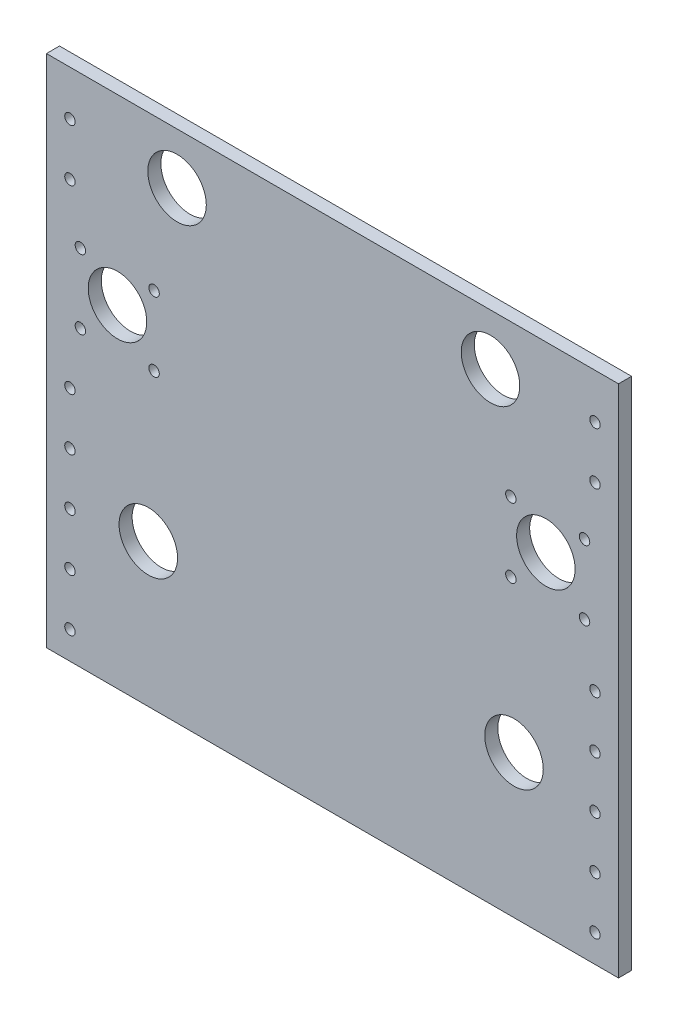
SolidWorks part; units mm, degrees
ref_plane "Front Plane" through (0, 0, 0) normal (0, 0, 1) x (1, 0, 0)
ref_plane "Top Plane" through (0, 0, 0) normal (0, 1, 0) x (1, 0, 0)
ref_plane "Right Plane" through (0, 0, 0) normal (1, 0, 0) x (0, 0, -1)
sketch "Sketch1" plane through (0, 0, 0) normal (0, 0, 1) x (1, 0, 0)
  line L1 (0, 0) -> (278.13, 0)
  line L2 (0, 0) -> (0, 250.19)
  line L3 (0, 250.19) -> (278.13, 250.19)
  line L4 (278.13, 0) -> (278.13, 250.19)
  dimension "D1" = 278.13
  dimension "D2" = 250.19
extrude "Boss-Extrude1" add sketch "Sketch1" along normal blind 6.35 contours L2 L1 L4 L3
sketch "Sketch2" plane through (0, 0, 6.35) normal (0, 0, 1) x (1, 0, 0)
  circle A0 centre (78.4492, 218.0515) radius 20.3285
  circle A1 centre (197.8327, 207.7025) radius 26.984
sketch "Sketch3" plane through (0, 0, 6.35) normal (0, 0, 1) x (1, 0, 0)
  line L0 (63.5, 225.298) -> (215.9, 225.298) construction
  line L1 (34.544, 161.544) -> (242.824, 161.544) construction
  line L2 (49.53, 69.596) -> (227.33, 69.596) construction
  line L3 (0, 250.19) -> (278.13, 250.19) construction
  line L5 (278.13, 0) -> (278.13, 250.19) construction
  line L6 (0, 0) -> (0, 250.19) construction
  circle A0 centre (63.5, 225.298) radius 14.224
  circle A1 centre (215.9, 225.298) radius 14.224
  circle A2 centre (34.544, 161.544) radius 14.224
  circle A3 centre (242.824, 161.544) radius 14.224
  circle A4 centre (49.53, 69.596) radius 14.224
  circle A5 centre (227.33, 69.596) radius 14.224
  dimension "D1" = 28.448
  dimension "D2" = 152.4
  dimension "D3" = 208.28
  dimension "D4" = 177.8
  dimension "D5" = 24.892
  dimension "D6" = 62.23
  dimension "D7" = 34.544
  dimension "D8" = 88.646
  dimension "D9" = 49.53
  dimension "D10" = 180.594
extrude "Cut-Extrude2" cut sketch "Sketch3" against normal through all both and the other way through all
sketch "Sketch5" plane through (0, 0, 6.35) normal (0, 0, 1) x (1, 0, 0)
  line L0 (0, 0) -> (0, 250.19) construction
  line L1 (278.13, 0) -> (278.13, 250.19) construction
  line L2 (0, 250.19) -> (278.13, 250.19) construction
  line L3 (0, 0) -> (278.13, 0) construction
  circle A0 centre (11.43, 228.346) radius 2.54
  circle A1 centre (11.43, 202.946) radius 2.54
  circle A2 centre (266.7, 202.946) radius 2.54
  circle A3 centre (266.7, 228.346) radius 2.54
  circle A4 centre (11.43, 115.062) radius 2.54
  circle A5 centre (11.43, 89.662) radius 2.54
  circle A6 centre (11.43, 64.262) radius 2.54
  circle A7 centre (11.43, 38.862) radius 2.54
  circle A8 centre (11.43, 13.462) radius 2.54
  circle A9 centre (266.7, 115.062) radius 2.54
  circle A10 centre (266.7, 89.662) radius 2.54
  circle A11 centre (266.7, 64.262) radius 2.54
  circle A12 centre (266.7, 38.862) radius 2.54
  circle A13 centre (266.7, 13.462) radius 2.54
  dimension "D1" = 5.08
  dimension "D2" = 11.43
  dimension "D3" = 11.43
  dimension "D4" = 11.43
  dimension "D5" = 11.43
  dimension "D6" = 11.43
  dimension "D7" = 11.43
  dimension "D8" = 11.43
  dimension "D9" = 11.43
  dimension "D10" = 11.43
  dimension "D11" = 11.43
  dimension "D12" = 11.43
  dimension "D13" = 11.43
  dimension "D14" = 11.43
  dimension "D15" = 11.43
  dimension "D16" = 21.844
  dimension "D17" = 25.4
  dimension "D18" = 21.844
  dimension "D19" = 25.4
  dimension "D20" = 13.462
  dimension "D21" = 25.4
  dimension "D22" = 25.4
  dimension "D23" = 25.4
  dimension "D24" = 25.4
  dimension "D25" = 13.462
  dimension "D26" = 25.4
  dimension "D27" = 25.4
  dimension "D28" = 25.4
  dimension "D29" = 25.4
extrude "Cut-Extrude4" cut sketch "Sketch5" against normal through all both and the other way through all
sketch "Sketch7" plane through (0, 0, 6.35) normal (0, 0, 1) x (1, 0, 0)
  line L0 (0, 250.19) -> (278.13, 250.19) construction
  line L1 (0, 0) -> (0, 250.19) construction
  line L2 (278.13, 0) -> (278.13, 250.19) construction
  circle A0 centre (16.51, 176.53) radius 2.54
  circle A1 centre (16.51, 142.748) radius 2.54
  circle A2 centre (52.324, 142.748) radius 2.54
  circle A3 centre (52.324, 176.53) radius 2.54
  circle A4 centre (225.806, 176.53) radius 2.54
  circle A5 centre (261.62, 176.53) radius 2.54
  circle A6 centre (225.806, 142.748) radius 2.54
  circle A7 centre (261.62, 142.748) radius 2.54
  dimension "D1" = 5.08
  dimension "D2" = 5.08
  dimension "D3" = 5.08
  dimension "D4" = 5.08
  dimension "D5" = 5.08
  dimension ".2" = 5.08
  dimension "D6" = 5.08
  dimension "D7" = 5.08
  dimension "D8" = 73.66
  dimension "D9" = 73.66
  dimension "D10" = 73.66
  dimension "D11" = 73.66
  dimension "D12" = 107.442
  dimension "D13" = 107.442
  dimension "D14" = 107.442
  dimension "D15" = 107.442
  dimension "D16" = 16.51
  dimension "D17" = 16.51
  dimension "D18" = 16.51
  dimension "D19" = 16.51
  dimension "D20" = 52.324
  dimension "D21" = 52.324
  dimension "D22" = 52.324
  dimension "D23" = 52.324
extrude "Cut-Extrude5" cut sketch "Sketch7" against normal through all both and the other way through all
equation "\"D10@Sketch5\"=\"D4@Sketch5\""
equation "\"D11@Sketch5\"=\"D4@Sketch5\""
equation "\"D12@Sketch5\"=\"D4@Sketch5\""
equation "\"D13@Sketch5\"=\"D4@Sketch5\""
equation "\"D14@Sketch5\"=\"D4@Sketch5\""
equation "\"D15@Sketch5\"=\"D4@Sketch5\""
equation "\"D5@Sketch5\"=\"D3@Sketch5\""
equation "\"D6@Sketch5\"=\"D4@Sketch5\""
equation "\"D7@Sketch5\"=\"D4@Sketch5\""
equation "\"D8@Sketch5\"=\"D4@Sketch5\""
equation "\"D9@Sketch5\"=\"D4@Sketch5\""
